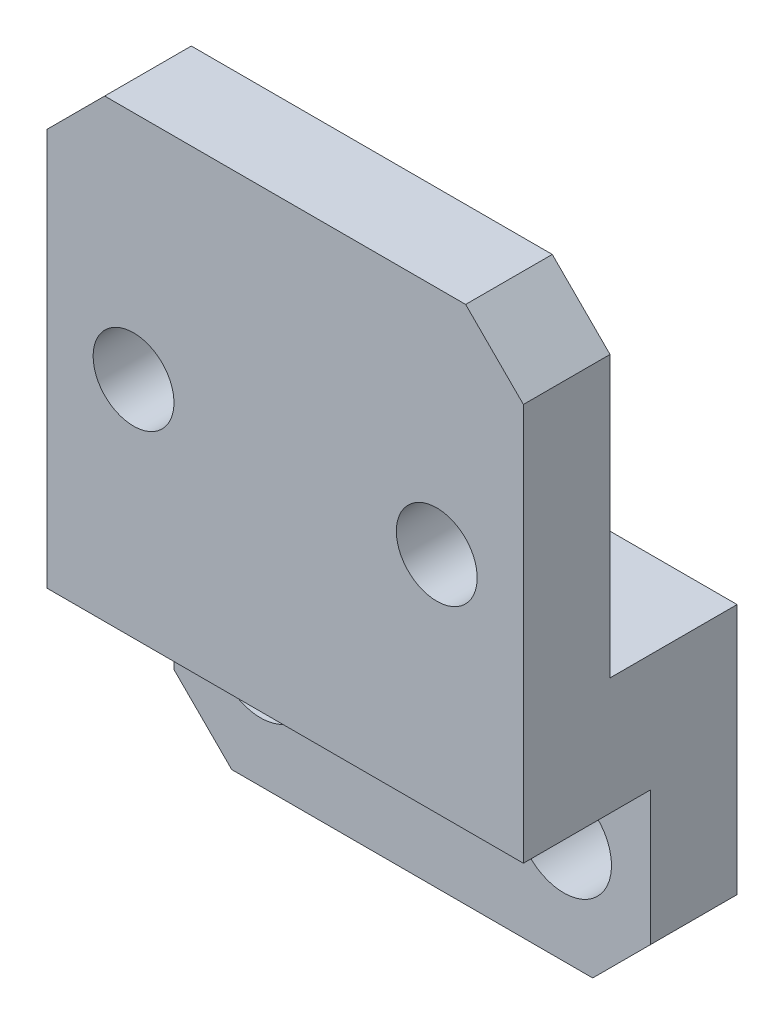
SolidWorks part; units mm, degrees
ref_plane "前视基准面" through (0, 0, 0) normal (0, 0, 1) x (1, 0, 0)
ref_plane "上视基准面" through (0, 0, 0) normal (0, 1, 0) x (1, 0, 0)
ref_plane "右视基准面" through (0, 0, 0) normal (1, 0, 0) x (0, 0, -1)
other "Configuration Table"
sketch "Sketch2" plane through (0, 0, 0) normal (0, 0, 1) x (1, 0, 0)
  line L0 (8.8001, -4.4586) -> (-8.5153, -4.4586) construction
  line L1 (8.25, 11.5) -> (-8.25, 11.5)
  line L2 (8.25, 11.5) -> (8.25, -4.2586)
  line L3 (8.25, -4.2586) -> (-8.25, -4.2586)
  line L4 (-8.25, 11.5) -> (-8.25, -4.2586)
  circle A0 centre (5.25, 3.5) radius 1.6 construction
  circle A1 centre (-5.25, 3.5) radius 1.6 construction
  dimension "D1" = 0.2
  dimension "D2" = 3
  dimension "D3" = 3
  dimension "D4" = 8
extrude "Boss-Extrude1" add sketch "Sketch2" along normal blind 3
sketch "Sketch3" plane through (0, 0, 0) normal (0, 0, -1) x (-1, 0, 0)
  line L0 (8.25, 11.5) -> (8.25, -4.2586) construction
  line L1 (-8.25, -4.2586) -> (8.25, -4.2586)
  line L2 (-8.25, -4.2586) -> (-8.25, -0.2)
  line L3 (-8.25, -0.2) -> (8.25, -0.2)
  line L4 (8.25, -4.2586) -> (8.25, -0.2)
  line L5 (8.1, 0) -> (-8.1, 0) construction
  dimension "D1" = 0.2
extrude "Boss-Extrude2" add sketch "Sketch3" along normal up to surface (1.4 mm away)
sketch "Sketch4" plane through (0, 0, -1.4) normal (0, 0, -1) x (-1, 0, 0)
  line L0 (8.5153, -10.9) -> (-8.5, -10.9) construction
  line L1 (-8.25, -0.2) -> (8.25, -0.2)
  line L2 (-8.25, -0.2) -> (-8.25, -10.9)
  line L3 (-8.25, -10.9) -> (8.25, -10.9)
  line L4 (8.25, -0.2) -> (8.25, -10.9)
  line L5 (8.25, -0.2) -> (8.25, -4.2586) construction
  circle A0 centre (-5.25, -7.2) radius 1.65
  circle A1 centre (5.25, -7.2) radius 1.65
  dimension "D2" = 3.3
  dimension "D3" = 3.3
  dimension "D1" = 0
extrude "Boss-Extrude3" add sketch "Sketch4" along normal blind 3
sketch "Sketch5" plane through (0, 0, 0) normal (0, 0, -1) x (-1, 0, 0)
  circle A0 centre (-5.25, 3.5) radius 1.4
  circle A1 centre (5.25, 3.5) radius 1.4
extrude "Cut-Extrude1" cut sketch "Sketch5" against normal blind 3
chamfer "Chamfer1" distance 2 angle 45 4 edges at (-8.25, 11.5, 1.5) (8.25, 11.5, 1.5) (-8.25, -10.9, -2.9) (8.25, -10.9, -2.9)
sketch "Sketch6" plane through (0, -0.2, 0) normal (0, 1, 0) x (1, 0, 0)
  circle A0 centre (0, 8.5) radius 4.45
  arc A1 (4.2426, 8.75) -> (0.25, 12.7426) centre (0, 8.5) ccw construction
  dimension "D1" = 0.2
extrude "Cut-Extrude2" cut sketch "Sketch6" against normal blind 17
